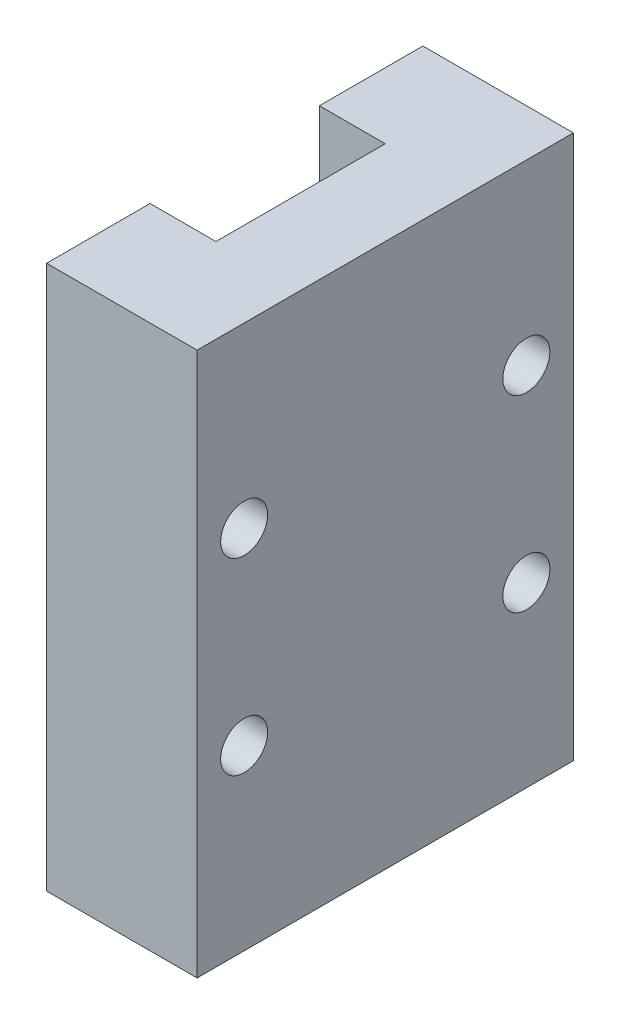
SolidWorks part; units mm, degrees
ref_plane "前视基准面" through (0, 0, 0) normal (0, 0, 1) x (1, 0, 0)
ref_plane "上视基准面" through (0, 0, 0) normal (0, 1, 0) x (1, 0, 0)
ref_plane "右视基准面" through (0, 0, 0) normal (1, 0, 0) x (0, 0, -1)
sketch "草图1" plane through (0, 0, 0) normal (1, 0, 0) x (0, 0, -1)
  line L1 (-10, -14.45) -> (10, -14.45)
  line L2 (-10, -14.45) -> (-10, 14.45)
  line L3 (-10, 14.45) -> (10, 14.45)
  line L4 (10, -14.45) -> (10, 14.45)
  line L5 (-10, -14.45) -> (10, 14.45) construction
  line L6 (-10, 14.45) -> (10, -14.45) construction
  point P0 (0, 0)
  dimension "D1" = 20
  dimension "D2" = 28.9
extrude "凸台-拉伸1" add sketch "草图1" along normal blind 8
sketch "草图2" plane through (0, 14.45, 0) normal (0, 1, 0) x (1, 0, 0)
  line L0 (0, 10) -> (0, -10) construction
  line L1 (0, 4.5) -> (3.5, 4.5)
  line L2 (0, 4.5) -> (0, -4.5)
  line L3 (0, -4.5) -> (3.5, -4.5)
  line L4 (3.5, 4.5) -> (3.5, -4.5)
  line L5 (8, 10) -> (0, 10) construction
  dimension "D1" = 3.5
  dimension "D2" = 9
  dimension "D3" = 5.5
extrude "切除-拉伸1" cut sketch "草图2" against normal through all
hole_wizard "M3 螺纹孔1" positions "草图4" profile "草图3" tap size "M3" standard "Gb"
sketch "草图4" plane through (8, 0, 0) normal (1, 0, 0) x (0, 0, -1)
  line L0 (-10, 14.45) -> (-10, -14.45) construction
  point P2 (-7.5, 5)
  point P4 (7.5, -5)
  point P6 (-7.5, -5)
  point P12 (7.5, 5)
  dimension "D1" = 15
  dimension "D2" = 15
  dimension "D3" = 2.5
  dimension "D4" = 2.5
  dimension "D5" = 10
  dimension "D6" = 5
sketch "草图3" plane through (8, 5, 7.5) normal (0, 1, 0) x (0, 0, -1)
  line L0 (0, 0) -> (0, 7.2511)
  line L1 (0, 7.2511) -> (1.25, 6.5)
  line L2 (1.25, 6.5) -> (1.25, 0)
  line L5 (1.25, 0) -> (0, 0)
  line L10 (0, 7.2511) -> (-1.25, 6.5) construction
  line L11 (0, -6.35) -> (0, 107.95) construction
  dimension "螺纹孔钻头直径" = 2.5
  dimension "螺纹孔钻头深度" = 6.5
  dimension "导头角度" = 118
cosmetic thread "孔螺蚊线1" parameters "D1"=5, "D2"=3
cosmetic thread "孔螺蚊线2" parameters "D1"=5, "D2"=3
cosmetic thread "孔螺蚊线3" parameters "D1"=5, "D2"=3
cosmetic thread "孔螺蚊线4" parameters "D1"=5, "D2"=3
